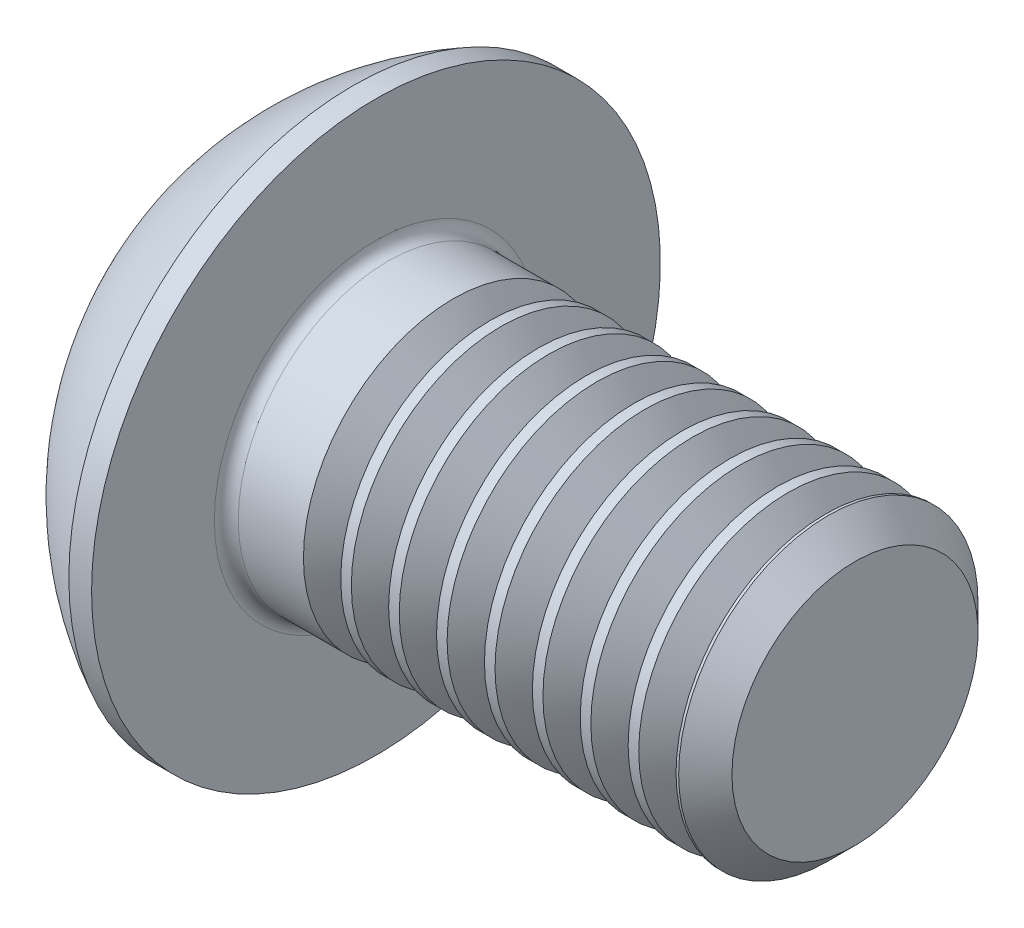
SolidWorks part; units mm, degrees
ref_plane "Plane1" through (0, 0, 0) normal (0, 0, 1) x (1, 0, 0)
ref_plane "Plane2" through (0, 0, 0) normal (0, 1, 0) x (1, 0, 0)
ref_plane "Plane3" through (0, 0, 0) normal (1, 0, 0) x (0, 0, -1)
sketch "BodySke" plane through (0, 0, 0) normal (0, 0, 1) x (1, 0, 0)
  line L0 (10.75, 0) -> (10.75, 2.055)
  line L1 (10.305, 2.5) -> (2.75, 2.5)
  line L2 (2.75, 2.5) -> (2.75, 4.75)
  line L3 (2.75, 4.75) -> (2.37, 4.75)
  line L4 (0, 0) -> (101.6, 0) construction
  line L5 (2.75, -4.75) -> (2.37, -4.75) construction
  line L6 (55.6768, -2.5) -> (2.75, -2.5) construction
  line L7 (10.75, 0) -> (0, 0)
  line L8 (0, 2.375) -> (0, -2.375) construction
  line L9 (0, 0) -> (0, 2.375)
  line L10 (10.75, 2.055) -> (10.305, 2.5)
  line L11 (10.75, -2.055) -> (10.305, -2.5) construction
  line L12 (3.55, 9.525) -> (3.55, -2.5) construction
  line L13 (2.75, 9.525) -> (2.75, -2.5) construction
  arc A1 (0, 2.375) -> (2.37, 4.75) centre (4.755, 0) cw
  dimension "Diameter" = 5
  dimension "Length" = 8
  dimension "Head_dia" = 9.5
  dimension "D1" = 4.75
  dimension "Head_ht" = 2.75
  dimension "Head_side_ht" = 0.38
  dimension "Minor_dia" = 4.11
  dimension "Body_ch_ang" = 45
  dimension "Advance" = 0.8
  dimension "Thread_nom" = 8
revolve "BaseBody" add sketch "BodySke" angle 360 about L4
cosmetic thread "ThreadCosmetic" [suppressed] parameters "Thread_length"=6.4, "Thread_minor"=4.11
fillet "Fillet1" radius 0.2 1 edges at (2.75, 0, 2.5)
sketch "Sketch2" plane through (0, 0, 0) normal (0, 0, 1) x (1, 0, 0)
  line L0 (0, 1.5) -> (1.56, 1.5)
  line L1 (1.56, 1.5) -> (2.426, 0)
  line L3 (2.426, 0) -> (0, 0)
  line L4 (0, 0) -> (0, 1.5)
  line L5 (0, -1.5) -> (1.56, -1.5) construction
  line L6 (0, 0) -> (47.625, 0) construction
  dimension "D2" = 60
  dimension "PreBroach_depth" = 1.56
  dimension "PreBroach_dia" = 3
revolve "PreBroach" cut sketch "Sketch2" angle 360 about L6
sketch "Sketch3" plane through (0, 0, 0) normal (1, 0, 0) x (0, 0, -1)
  line L0 (-1.5, -0.866) -> (-1.5, 0.866)
  line L1 (-1.5, 0.866) -> (0, 1.7321)
  line L2 (0, 1.7321) -> (1.5, 0.866)
  line L3 (1.5, 0.866) -> (1.5, -0.866)
  line L4 (1.5, -0.866) -> (0, -1.7321)
  line L5 (0, -1.7321) -> (-1.5, -0.866)
  dimension "Hex_size" = 3
  dimension "D3" = 3
  dimension "D1" = 1.5
  dimension "D2" = 1.5
extrude "Hex" cut sketch "Sketch3" along normal blind 1.56
sketch "ThdSchSke" plane through (0, 0, 0) normal (0, 0, 1) x (1, 0, 0)
  line L0 (4.35, -2.055) -> (4.0384, -2.5)
  line L1 (4.35, -2.055) -> (4.6616, -2.5)
  line L2 (4.6616, -2.5) -> (4.6616, -3.125)
  line L3 (-3.175, 0) -> (5.1513, 0) construction
  line L5 (4.6616, -3.125) -> (4.0384, -3.125)
  line L6 (4.0384, -3.125) -> (4.0384, -2.5)
  dimension "Diameter" = 5
  dimension "Thread_minor" = 4.11
  dimension "SideAngle" = 55
  dimension "VeeAngle" = 70
  dimension "Overcut" = 6.25
  dimension "Start" = 4.35
revolve "ThreadSchematic" cut sketch "ThdSchSke" angle 360 about L3
pattern_linear "ThdSchPat" count 8 spacing 0.8 along (1, 0, 0) of "ThreadSchematic"
equation "\"D1@BodySke\" = \"Head_dia@BodySke\" * .5"
equation "\"Thread_minor@ThreadCosmetic\" = \"Minor_dia@BodySke\""
equation "\"D1@Sketch3\" = \"Hex_size@Sketch3\" / 2"
equation "\"D2@Sketch3\" = \"D1@Sketch3\""
equation "\"D3@Sketch3\" = \"Hex_size@Sketch3\""
equation "\"Thread_length@ThreadCosmetic\" = ((sgn( (\"Length@BodySke\" - \"Advance@BodySke\" * 2.0) - \"Thread_nom@BodySke\" )-1)*( (\"Length@BodySke\" - \"Advance@BodySke\" * 2.0) - \"Thread_nom@BodySke\" ))/-2+ \"Thread_nom@BodySke\""
equation "\"Thread_minor@ThdSchSke\" = \"Minor_dia@BodySke\""
equation "\"Diameter@ThdSchSke\" = \"Diameter@BodySke\""
equation "\"Overcut@ThdSchSke\" = \"Diameter@BodySke\" * 1.25"
equation "\"Start@ThdSchSke\" = \"Head_ht@BodySke\" + \"Length@BodySke\" - \"Thread_length@ThreadCosmetic\"  '---Non-countersunk---"
equation "\"Num_threads@ThdSchPat\" = int( \"Thread_length@ThreadCosmetic\" / \"Advance@BodySke\" + 0.999 )  + 1"
equation "\"Advance@ThdSchPat\" = \"Thread_length@ThreadCosmetic\" /  (\"Num_threads@ThdSchPat\" - 1) 'relax it"
equation "\"Num_threads@ThdSchPat\" = \"Num_threads@ThdSchPat\" - sgn( \"Num_threads@ThdSchPat\" - 1) '---chamfered tips only---"
